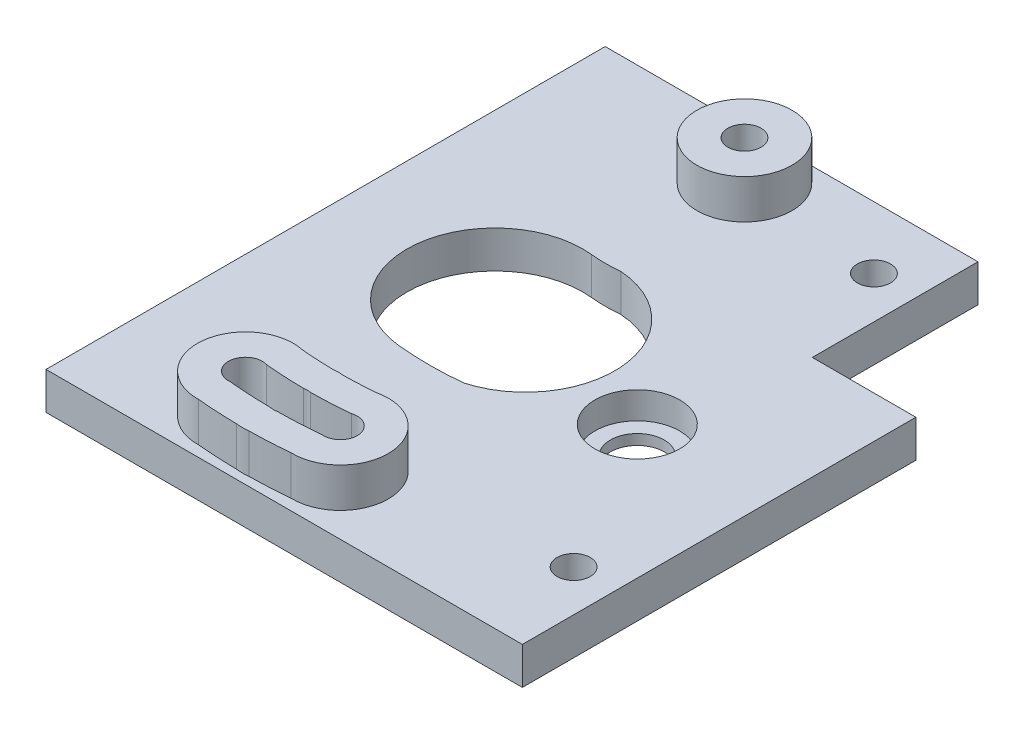
SolidWorks part; units mm, degrees
ref_plane "前视基准面" through (0, 0, 0) normal (0, 0, 1) x (1, 0, 0)
ref_plane "上视基准面" through (0, 0, 0) normal (0, 1, 0) x (1, 0, 0)
ref_plane "右视基准面" through (0, 0, 0) normal (1, 0, 0) x (0, 0, -1)
other "Configuration Table"
sketch "草图1" plane through (0, 0, 0) normal (0, 1, 0) x (1, 0, 0)
  line L1 (0, 0) -> (46, 0)
  line L2 (0, 0) -> (0, 54)
  line L3 (0, 54) -> (46, 54)
  line L4 (46, 0) -> (46, 54)
  dimension "D1" = 46
  dimension "D2" = 54
extrude "凸台-拉伸1" add sketch "草图1" along normal blind 3.6
sketch "草图2" plane through (0, 0, 0) normal (0, -1, 0) x (-1, 0, 0)
  line L0 (0, 54) -> (0, 0) construction
  line L1 (-46, 54) -> (0, 54) construction
  circle A0 centre (-18.15, 49.3) radius 1.6
  circle A1 centre (-18.15, 5.45) radius 1.6344
  circle A2 centre (-18.15, 27.375) radius 8.5
  circle A3 centre (-33.15, 23.95) radius 4.1
  point P6 (0, 27)
  point P9 (-23, 54)
  dimension "D7" = 17
  dimension "D10" = 8.2
  dimension "D11" = 3.2
  dimension "D1" = 22.3
  dimension "D2" = 4.85
  dimension "D3" = 0
  dimension "D4" = 43.85
  dimension "D5" = 0
  dimension "D6" = 21.925
  dimension "D8" = 15
  dimension "D9" = 18.5
extrude "切除-拉伸1" cut sketch "草图2" against normal blind 3.6
sketch "草图4" plane through (0, 0, 0) normal (0, -1, 0) x (-1, 0, 0)
  circle A0 centre (-33.15, 23.95) radius 4.1
  circle A1 centre (-33.15, 23.95) radius 2.6
  dimension "D1" = 5.2
extrude "凸台-拉伸2" add sketch "草图4" against normal blind 1
sketch "草图5" plane through (0, 3.6, 0) normal (0, 1, 0) x (1, 0, 0)
  line L0 (46, 0) -> (46, 54) construction
  line L1 (46, 54) -> (36, 54)
  line L2 (46, 54) -> (46, 38)
  line L3 (46, 38) -> (36, 38)
  line L4 (36, 54) -> (36, 38)
  line L5 (46, 54) -> (0, 54) construction
  dimension "D1" = 16
  dimension "D2" = 10
extrude "切除-拉伸2" cut sketch "草图5" against normal blind 4
sketch "草图6" plane through (0, 0, 0) normal (0, -1, 0) x (-1, 0, 0)
  circle A0 centre (-18.15, 49.3) radius 43.85 construction
  arc A1 (-22.5629, 4.0647) -> (-13.7371, 4.0647) centre (-18.15, 49.3) ccw
  arc A2 (-22.2405, 7.2485) -> (-14.0595, 7.2485) centre (-18.15, 49.3) ccw
  arc A3 (-13.7371, 4.0647) -> (-14.0595, 7.2485) centre (-13.5664, 5.6902) ccw
  arc A4 (-22.2405, 7.2485) -> (-22.5629, 4.0647) centre (-22.7336, 5.6902) ccw
  circle A5 centre (-18.15, 5.45) radius 1.6344
  circle A6 centre (-18.15, 5.45) radius 1.6344 construction
  circle A7 centre (-18.15, 49.3) radius 21.925 construction
  circle A8 centre (-18.15, 49.3) radius 45.45 construction
  circle A9 centre (-18.15, 49.3) radius 42.25 construction
  arc A10 (-21.3303, 19.0417) -> (-14.9697, 19.0417) centre (-18.15, 49.3) ccw
  arc A11 (-19.5533, 35.9485) -> (-16.7467, 35.9485) centre (-18.15, 49.3) ccw
  arc A13 (-19.5533, 35.9485) -> (-21.3303, 19.0417) centre (-18.9549, 27.3388) ccw
  arc A14 (-14.9697, 19.0417) -> (-16.7467, 35.9485) centre (-15.8582, 27.4951) ccw
  point P5 (24.1, 49.3)
  point P8 (27.3, 49.3)
  point P15 (-18.15, 49.3)
  point P18 (-18.15, 49.3)
  point P31 (-18.15, 49.3)
  point P34 (-18.15, 49.3)
  point P38 (0, 0)
  dimension "D1" = 1.6
  dimension "D2" = 1.6
  dimension "D3" = 0
  dimension "D4" = 2
  dimension "D5" = 2
extrude "切除-拉伸3" cut sketch "草图6" against normal blind 10
sketch "草图7" plane through (0, 3.6, 0) normal (0, 1, 0) x (1, 0, 0)
  circle A1 centre (18.15, 49.3) radius 4.6
  circle A2 centre (18.15, 49.3) radius 1.6
  circle A3 centre (18.15, 49.3) radius 1.6
  arc A48 (18.6834, 10.0536) -> (21.7219, 10.2129) centre (18.15, 49.3) ccw
  arc A49 (18.6834, 10.0536) -> (17.6166, 10.0536) centre (18.15, 5.45) ccw
  arc A50 (14.5781, 10.2129) -> (17.6166, 10.0536) centre (18.15, 49.3) ccw
  arc A51 (14.5781, 10.2129) -> (13.6753, 1.0571) centre (13.5664, 5.6902) ccw
  arc A52 (17.5574, 0.8536) -> (18.7426, 0.8536) centre (18.15, 5.45) ccw
  arc A53 (13.6753, 1.0571) -> (17.5574, 0.8536) centre (18.15, 49.3) ccw
  arc A54 (18.7426, 0.8536) -> (22.6247, 1.0571) centre (18.15, 49.3) ccw
  arc A55 (22.6247, 1.0571) -> (21.7219, 10.2129) centre (22.7336, 5.6902) ccw
  arc A56 (18.6834, 10.0536) -> (21.7219, 10.2129) centre (18.15, 49.3) ccw
  arc A57 (18.6834, 10.0536) -> (17.6166, 10.0536) centre (18.15, 5.45) ccw
  arc A58 (14.5781, 10.2129) -> (17.6166, 10.0536) centre (18.15, 49.3) ccw
  arc A59 (14.5781, 10.2129) -> (13.6753, 1.0571) centre (13.5664, 5.6902) ccw
  arc A60 (17.5574, 0.8536) -> (18.7426, 0.8536) centre (18.15, 5.45) ccw
  arc A61 (13.6753, 1.0571) -> (17.5574, 0.8536) centre (18.15, 49.3) ccw
  arc A62 (18.7426, 0.8536) -> (22.6247, 1.0571) centre (18.15, 49.3) ccw
  arc A63 (22.6247, 1.0571) -> (21.7219, 10.2129) centre (22.7336, 5.6902) ccw
  arc A92 (18.4775, 7.0513) -> (22.2405, 7.2485) centre (18.15, 49.3) ccw
  arc A93 (22.5629, 4.0647) -> (22.2405, 7.2485) centre (22.7336, 5.6902) ccw
  arc A94 (18.4897, 3.8513) -> (22.5629, 4.0647) centre (18.15, 49.3) ccw
  arc A95 (17.8103, 3.8513) -> (18.4897, 3.8513) centre (18.15, 5.45) ccw
  arc A96 (13.7371, 4.0647) -> (17.8103, 3.8513) centre (18.15, 49.3) ccw
  arc A97 (14.0595, 7.2485) -> (13.7371, 4.0647) centre (13.5664, 5.6902) ccw
  arc A98 (14.0595, 7.2485) -> (17.8225, 7.0513) centre (18.15, 49.3) ccw
  arc A99 (18.4775, 7.0513) -> (17.8225, 7.0513) centre (18.15, 5.45) ccw
  dimension "D1" = 0
  dimension "D2" = 3
  dimension "D3" = 3
  dimension "D4" = 3
extrude "凸台-拉伸3" add sketch "草图7" along normal blind 3.8
sketch "草图10" plane through (0, 3.6, 0) normal (0, 1, 0) x (1, 0, 0)
  line L0 (46, 0) -> (46, 38) construction
  line L1 (0, 0) -> (46, 0) construction
  circle A1 centre (42, 8.95) radius 1.6
  dimension "D1" = 4
  dimension "D2" = 8.95
extrude "切除-拉伸6" cut sketch "草图10" against normal through all
sketch "草图11" plane through (0, 3.6, 0) normal (0, 1, 0) x (1, 0, 0)
  line L1 (36, 54) -> (0, 54) construction
  circle A0 centre (31.95, 48) radius 1.6
  circle A1 centre (18.15, 49.3) radius 4.6 construction
  dimension "D1" = 3.2
  dimension "D2" = 13.8
  dimension "D3" = 6
extrude "切除-拉伸7" cut sketch "草图11" against normal through all
equation "\"D6@草图2\"=\"D4@草图2\"/2"
equation "\"D1@凸台-拉伸2\"=3.60-2.6"
